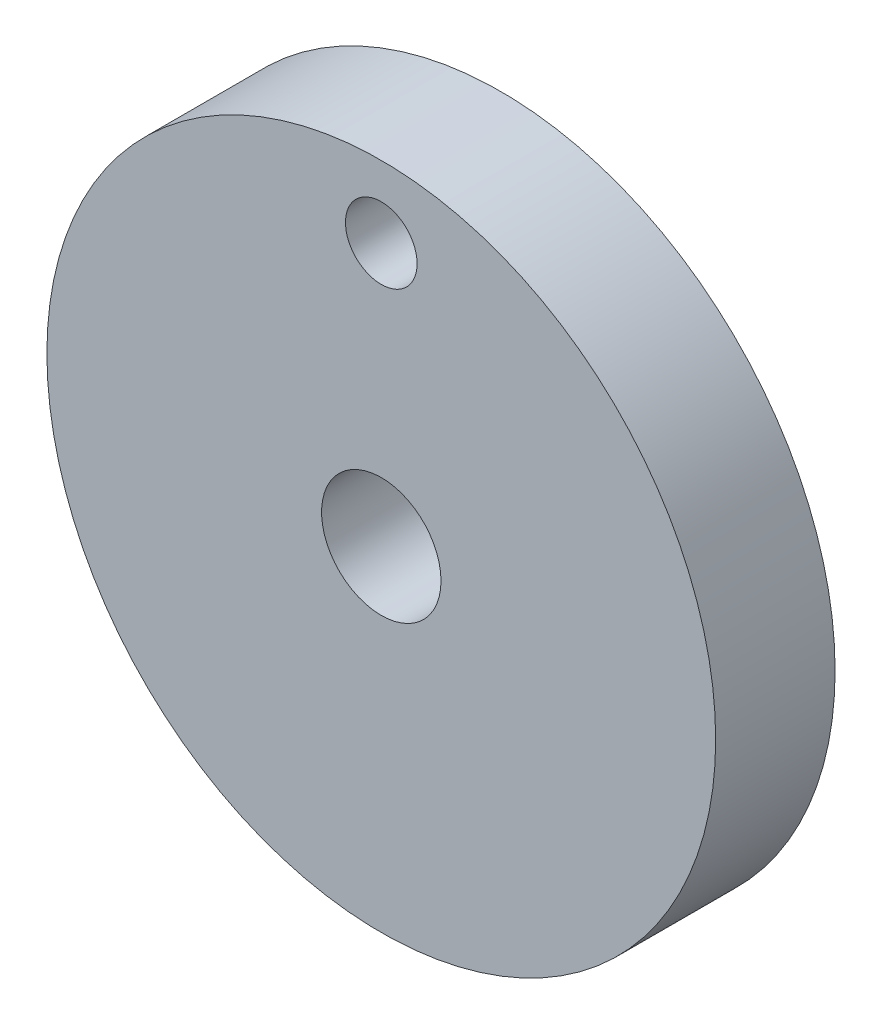
SolidWorks part; units mm, degrees
ref_plane "Front Plane" through (0, 0, 0) normal (0, 0, 1) x (1, 0, 0)
ref_plane "Top Plane" through (0, 0, 0) normal (0, 1, 0) x (1, 0, 0)
ref_plane "Right Plane" through (0, 0, 0) normal (1, 0, 0) x (0, 0, -1)
sketch "Sketch1" plane through (0, 0, 0) normal (0, 0, 1) x (1, 0, 0)
  circle A0 centre (0, 0) radius 14
  dimension "D1" = 28
extrude "Boss-Extrude1" add sketch "Sketch1" along normal blind 5
sketch "Sketch2" plane through (0, 0, 0) normal (0, 0, 1) x (1, 0, 0)
  circle A0 centre (0, 11) radius 1.5
  circle A1 centre (0, 0) radius 2.5
  dimension "D1" = 3
  dimension "D3" = 5
  dimension "D2" = 11
extrude "Cut-Extrude1" cut sketch "Sketch2" along normal through all
